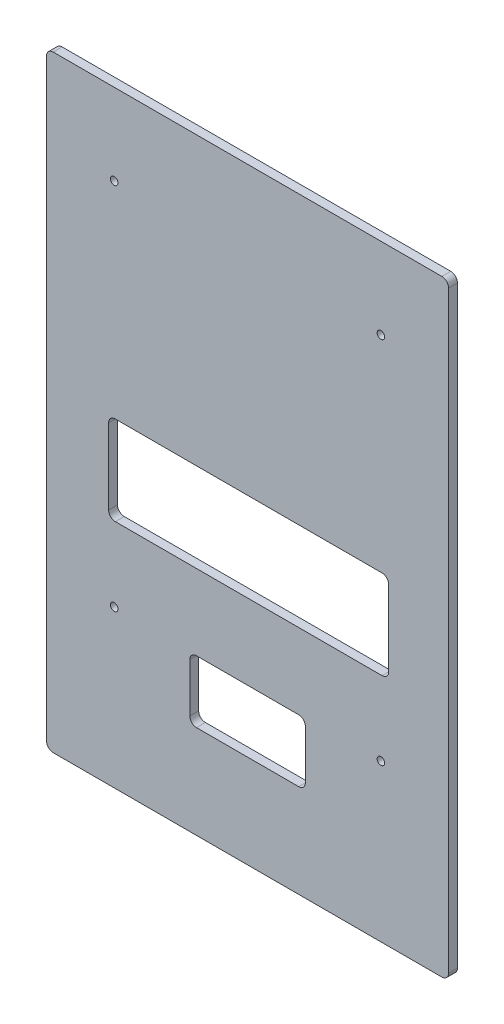
SolidWorks part; units mm, degrees
material "Verre"
ref_plane "Plan de face" through (0, 0, 0) normal (0, 0, 1) x (1, 0, 0)
ref_plane "Plan de dessus" through (0, 0, 0) normal (0, 1, 0) x (1, 0, 0)
ref_plane "Plan de droite" through (0, 0, 0) normal (1, 0, 0) x (0, 0, -1)
sketch "Esquisse1" plane through (0, 0, 0) normal (0, 0, 1) x (1, 0, 0)
  line L1 (0, 0) -> (180.86, 0)
  line L2 (0, 0) -> (0, 273)
  line L3 (0, 273) -> (180.86, 273)
  line L4 (180.86, 0) -> (180.86, 273)
  line L5 (64.43, 70) -> (116.43, 70)
  line L6 (64.43, 70) -> (64.43, 42)
  line L7 (64.43, 42) -> (116.43, 42)
  line L8 (116.43, 70) -> (116.43, 42)
  line L9 (27.93, 144) -> (153.93, 144)
  line L10 (27.93, 144) -> (27.93, 104)
  line L11 (27.93, 104) -> (153.93, 104)
  line L12 (153.93, 144) -> (153.93, 104)
  circle A0 centre (30.43, 236.5) radius 1.5
  circle A1 centre (150.43, 236.5) radius 1.5
  circle A2 centre (30.43, 70.5) radius 1.5
  circle A3 centre (150.43, 70.5) radius 1.5
  dimension "D5" = 3
  dimension "D8" = 3
  dimension "D13" = 3
  dimension "D14" = 3
  dimension "D1" = 180.86
  dimension "D2" = 273
  dimension "D3" = 30.43
  dimension "D4" = 36.5
  dimension "D6" = 36.5
  dimension "D7" = 30.43
  dimension "D9" = 30.43
  dimension "D10" = 30.43
  dimension "D11" = 70.5
  dimension "D12" = 70.5
  dimension "D15" = 64.43
  dimension "D16" = 42
  dimension "D17" = 28
  dimension "D18" = 34
  dimension "D19" = 40
  dimension "D20" = 52
  dimension "D21" = 27.93
  dimension "D22" = 26.93
extrude "Boss.-Extru.1" add sketch "Esquisse1" along normal blind 4
hole_wizard "Dégagement M31" positions "Esquisse2" profile "Esquisse3" hole size "M3" standard "ISO" end condition through all
sketch "Esquisse2" plane through (0, 0, 4) normal (0, 0, 1) x (1, 0, 0)
  point P0 (30.43, 236.5)
  point P3 (150.43, 236.5)
  point P6 (150.43, 70.5)
  point P9 (30.43, 70.5)
sketch "Esquisse3" plane through (30.43, 236.5, 4) normal (1, 0, 0) x (0, -1, 0)
  line L0 (0, 0) -> (0, 4)
  line L1 (0, 4) -> (1.7, 4)
  line L2 (1.7, 4) -> (1.7, 0)
  line L5 (1.7, 0) -> (0, 0)
  line L11 (0, -6.35) -> (0, 107.95) construction
  dimension "Diamètre du perçage jusqu'au prochain" = 3.4
  dimension "Profondeur du perçage jusqu'au prochain" = 4
fillet "Congé1" radius 3 12 edges at (0, 0, 2) (180.86, 0, 2) (116.43, 42, 2) (64.43, 42, 2) (116.43, 70, 2) (64.43, 70, 2) (153.93, 104, 2) (27.93, 104, 2) (153.93, 144, 2) (27.93, 144, 2) (180.86, 273, 2) (0, 273, 2)
equation "\"D7@Esquisse1\"=\"D3@Esquisse1\""
equation "\"D9@Esquisse1\"=\"D3@Esquisse1\""
equation "\"D10@Esquisse1\"=\"D3@Esquisse1\""
equation "\"D12@Esquisse1\"=\"D11@Esquisse1\""
equation "\"D13@Esquisse1\"=\"D5@Esquisse1\""
equation "\"D14@Esquisse1\"=\"D8@Esquisse1\""
